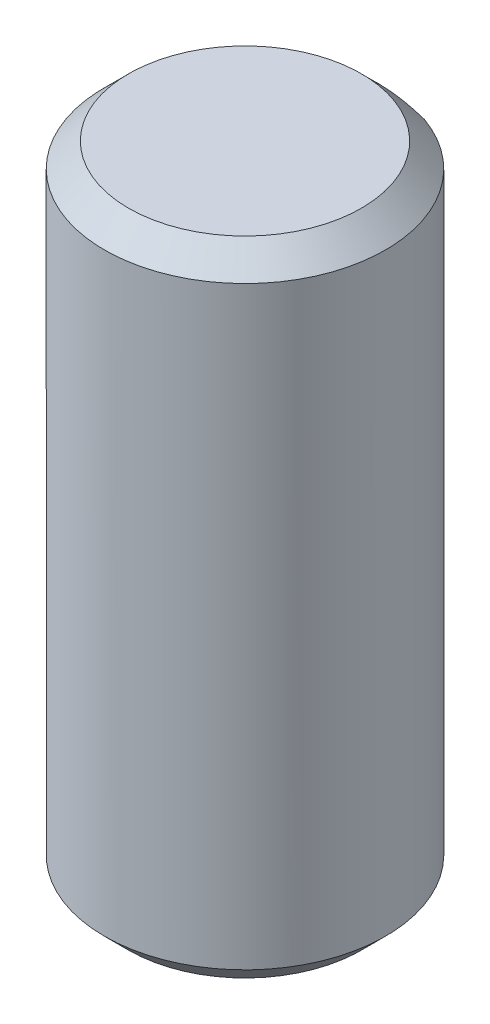
SolidWorks part; units mm, degrees
ref_plane "Front Plane" through (0, 0, 0) normal (0, 0, 1) x (1, 0, 0)
ref_plane "Top Plane" through (0, 0, 0) normal (0, 1, 0) x (1, 0, 0)
ref_plane "Right Plane" through (0, 0, 0) normal (1, 0, 0) x (0, 0, -1)
sketch "Sketch1" plane through (0, 0, 0) normal (0, 1, 0) x (1, 0, 0)
  circle A0 centre (0, 0) radius 17.5
  dimension "D1" = 35
extrude "Boss-Extrude1" add sketch "Sketch1" along normal blind 80
chamfer "Chamfer1" distance 3 angle 45 2 edges at (0, 0, 17.5) (0, 80, 17.5)
sketch "Sketch2" plane through (0, 0, 0) normal (0, 1, 0) x (1, 0, 0)
  line L1 (17.5, 21.5) -> (-17.5, 21.5)
  line L2 (17.5, 21.5) -> (17.5, 16.5)
  line L3 (17.5, 16.5) -> (-17.5, 16.5)
  line L4 (-17.5, 21.5) -> (-17.5, 16.5)
  line L5 (17.5, 21.5) -> (-17.5, 16.5) construction
  line L6 (17.5, 16.5) -> (-17.5, 21.5) construction
  circle A0 centre (0, 0) radius 17.5 construction
  point P4 (0, 19)
  point P9 (0, 17.5)
  dimension "D1" = 1
  dimension "D2" = 5
extrude "Cut-Extrude1" cut sketch "Sketch2" against normal through all and the other way through all
sketch "Sketch3" plane through (0, 0, 0) normal (0, 0, 1) x (1, 0, 0)
  line L0 (-5.831, 77) -> (-5.831, 3) construction
  circle A0 centre (0, 40) radius 5
  point P3 (-5.831, 40)
  dimension "D1" = 10
